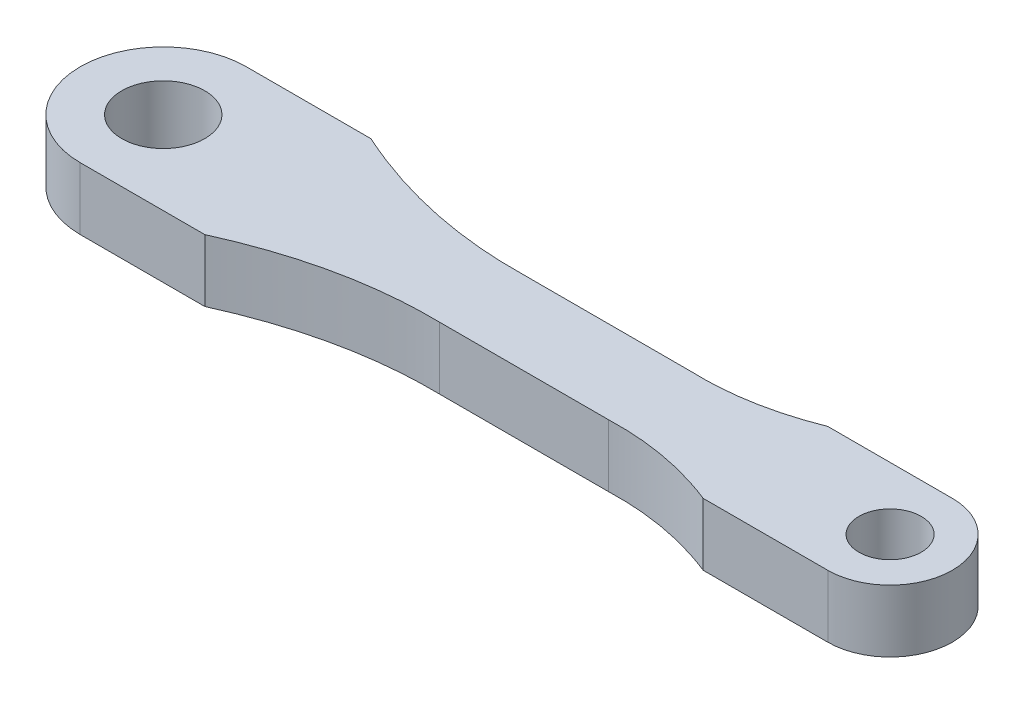
SolidWorks part; units mm, degrees
ref_plane "Front Plane" through (0, 0, 0) normal (0, 0, 1) x (1, 0, 0)
ref_plane "Top Plane" through (0, 0, 0) normal (0, 1, 0) x (1, 0, 0)
ref_plane "Right Plane" through (0, 0, 0) normal (1, 0, 0) x (0, 0, -1)
sketch "Sketch1" plane through (0, 0, 0) normal (0, 1, 0) x (1, 0, 0)
  line L0 (-17.5, 0) -> (17.5, 0) construction
  line L2 (-17.5, -4) -> (-11.5, -4)
  line L4 (-2.2009, -2) -> (5.9474, -2)
  line L6 (11.5, -3) -> (17.5, -3)
  line L9 (11.5, 3) -> (17.5, 3)
  line L10 (-2.2009, 2) -> (5.9474, 2)
  line L12 (-17.5, 4) -> (-11.5, 4)
  circle A0 centre (-17.5, 0) radius 2
  arc A1 (-17.5, 4) -> (-17.5, -4) centre (-17.5, 0) ccw
  circle A2 centre (17.5, 0) radius 1.5
  arc A3 (17.5, -3) -> (17.5, 3) centre (17.5, 0) ccw
  spline S0 degree 3 poles (-11.5, -4) (-8.4319, -2.6106) (-5.3322, -1.9439) (-2.2009, -2) knots 0 0 0 0 0.616301 0.616301 0.616301 0.616301
  spline S1 degree 3 poles (-11.5, 4) (-8.4319, 2.6106) (-5.3322, 1.9439) (-2.2009, 2) knots 0 0 0 0 0.616301 0.616301 0.616301 0.616301
  spline S2 degree 3 poles (11.5, 3) (9.6731, 2.2698) (7.8223, 1.9364) (5.9474, 2) knots 0 0 0 0 0.698718 0.698718 0.698718 0.698718
  spline S3 degree 3 poles (11.5, -3) (9.6731, -2.2698) (7.8223, -1.9364) (5.9474, -2) knots 0 0 0 0 0.698718 0.698718 0.698718 0.698718
  dimension "D7" = 4
  dimension "D8" = 3
  dimension "D1" = 6
  dimension "D2" = 6
  dimension "D3" = 35
  dimension "D4" = 17.5
  dimension "D5" = 4
  dimension "D6" = 3
  dimension "2" = 2
extrude "Boss-Extrude1" add sketch "Sketch1" along normal blind 3
